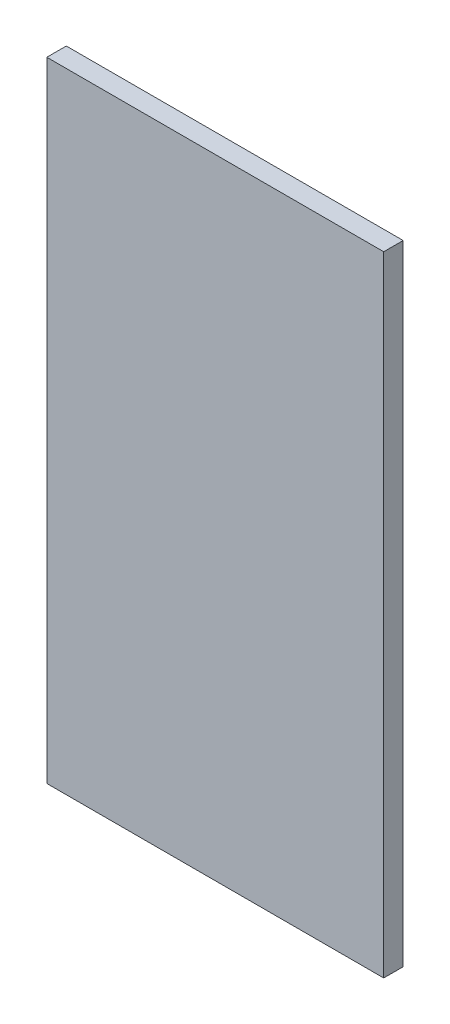
SolidWorks part; units mm, degrees
ref_plane "前基準面" through (0, 0, 0) normal (0, 0, 1) x (1, 0, 0)
ref_plane "上基準面" through (0, 0, 0) normal (0, 1, 0) x (1, 0, 0)
ref_plane "右基準面" through (0, 0, 0) normal (1, 0, 0) x (0, 0, -1)
sketch "草圖1" plane through (0, 0, 0) normal (0, 0, 1) x (1, 0, 0)
  line L1 (-173, 323) -> (173, 323)
  line L2 (-173, 323) -> (-173, -323)
  line L3 (-173, -323) -> (173, -323)
  line L4 (173, 323) -> (173, -323)
  point P4 (0, 323)
  point P6 (-173, 0)
  dimension "D1" = 346
  dimension "D2" = 646
extrude "填料-伸長1" add sketch "草圖1" along normal blind 20
